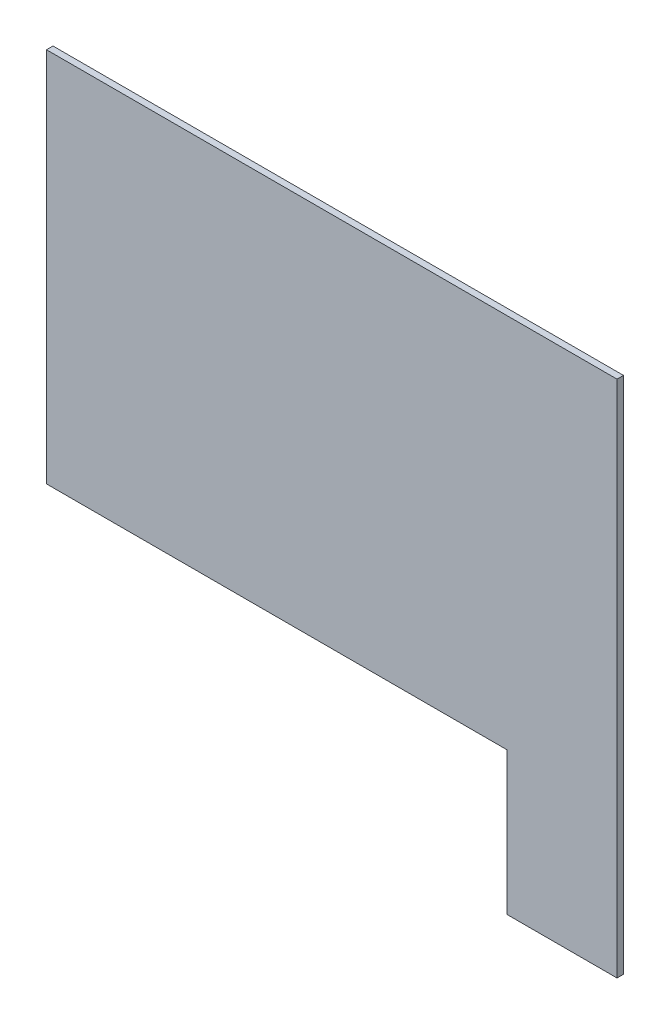
SolidWorks part; units mm, degrees
ref_plane "Alzado" through (0, 0, 0) normal (0, 0, 1) x (1, 0, 0)
ref_plane "Planta" through (0, 0, 0) normal (0, 1, 0) x (1, 0, 0)
ref_plane "Vista lateral" through (0, 0, 0) normal (1, 0, 0) x (0, 0, -1)
sketch "Croquis1" plane through (0, 0, 0) normal (0, 0, 1) x (-1, 0, 0)
  line L19 (-143.5867, 402.2958) -> (-228.5867, 402.2958)
  line L21 (-143.5867, 292.2958) -> (-143.5867, 402.2958)
  line L22 (-228.5867, 2.2958) -> (-228.5867, 402.2958)
  line L24 (211.4133, 2.2958) -> (211.4133, 292.2958)
  line L26 (-228.5867, 2.2958) -> (211.4133, 2.2958)
  line L27 (211.4133, 292.2958) -> (-143.5867, 292.2958)
  dimension "D1" = 400
  dimension "D2" = 440
  dimension "D3" = 85
  dimension "D4" = 290
extrude "Saliente-Extruir1" add sketch "Croquis1" along normal blind 5
